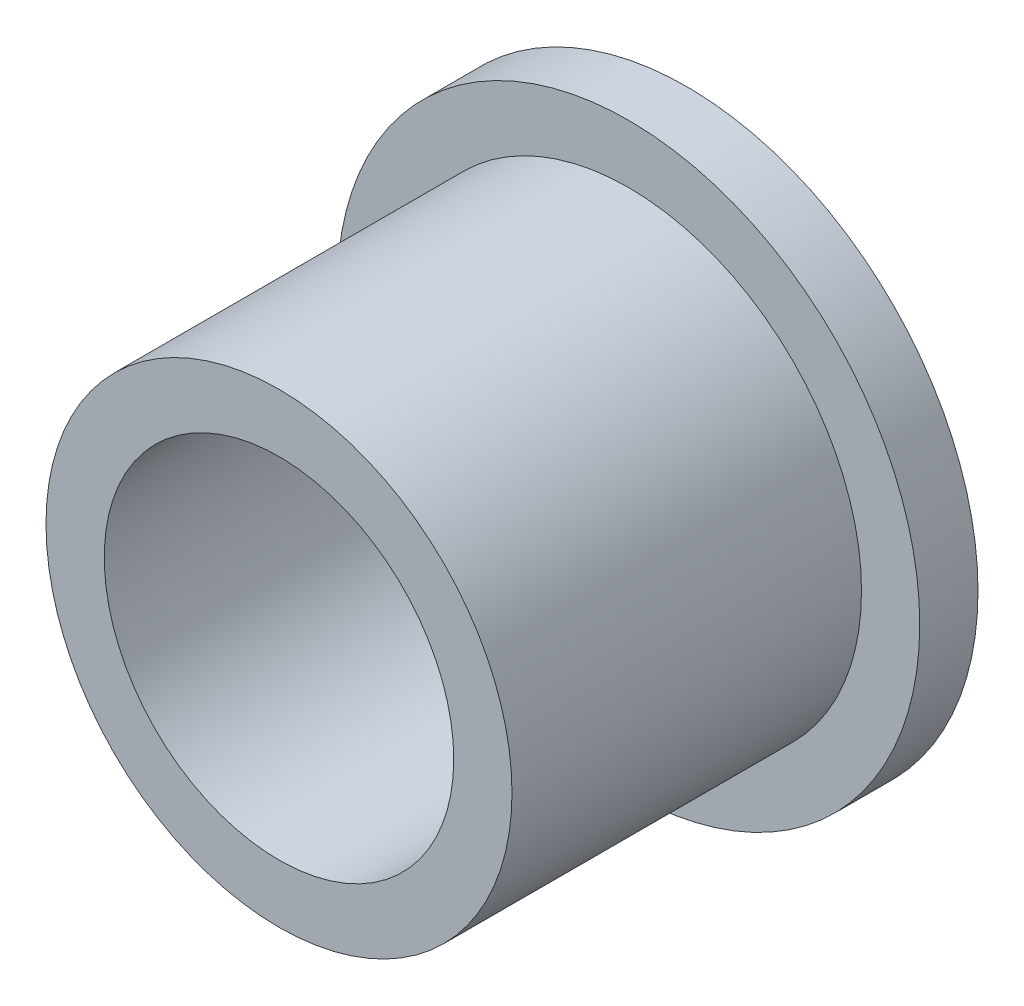
SolidWorks part; units mm, degrees
ref_plane "Front Plane" through (0, 0, 0) normal (0, 0, 1) x (1, 0, 0)
ref_plane "Top Plane" through (0, 0, 0) normal (0, 1, 0) x (1, 0, 0)
ref_plane "Right Plane" through (0, 0, 0) normal (1, 0, 0) x (0, 0, -1)
sketch "Sketch2" plane through (0, 0, 0) normal (0, 0, 1) x (1, 0, 0)
  circle A0 centre (0, 0) radius 15
  dimension "D1" = 30
extrude "Boss-Extrude1" add sketch "Sketch2" along normal blind 3
sketch "Sketch3" plane through (0, 0, 3) normal (0, 0, 1) x (1, 0, 0)
  circle A0 centre (0, 0) radius 12
  dimension "D1" = 24
extrude "Boss-Extrude2" add sketch "Sketch3" along normal blind 18
sketch "Sketch4" plane through (0, 0, 21) normal (0, 0, 1) x (1, 0, 0)
  circle A0 centre (0, 0) radius 9
  dimension "D1" = 18
extrude "Cut-Extrude1" cut sketch "Sketch4" against normal up to surface (21 mm away) up to face at (15, 0, 0)
